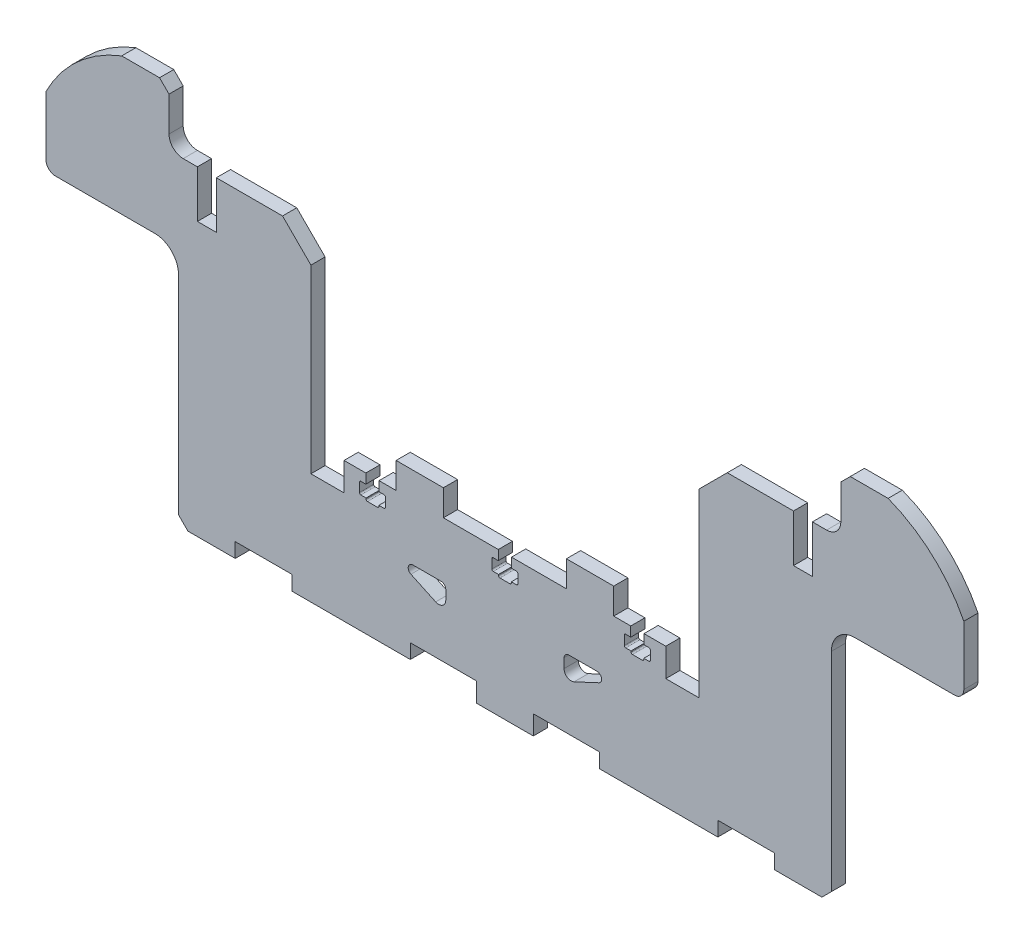
SolidWorks part; units mm, degrees
ref_plane "前视基准面" through (0, 0, 0) normal (0, 0, 1) x (1, 0, 0)
ref_plane "上视基准面" through (0, 0, 0) normal (0, 1, 0) x (1, 0, 0)
ref_plane "右视基准面" through (0, 0, 0) normal (1, 0, 0) x (0, 0, -1)
sketch "草图1" plane through (0, 0, 0) normal (0, 0, 1) x (-1, 0, 0)
  line L2 (-187.1418, -9.2028) -> (-181.9079, -11.6453)
  line L4 (-189.2762, -12.5515) -> (-189.2762, -10.5621)
  line L6 (-182.3308, -13.5515) -> (-188.2762, -13.5515)
  line L8 (-221.6444, -11.6453) -> (-216.4105, -9.2028)
  line L10 (-214.2762, -10.5621) -> (-214.2762, -12.5515)
  line L12 (-215.2762, -13.5515) -> (-221.2216, -13.5515)
  line L188 (-132.7762, 2.0293) -> (-134.7762, 4.0293)
  line L189 (-134.7762, 4.0293) -> (-144.7762, 4.0293)
  line L190 (-144.7762, 4.0293) -> (-144.7762, 0.9485)
  line L191 (-144.7762, 0.9485) -> (-156.7762, 0.9485)
  line L192 (-156.7762, 0.9485) -> (-156.7762, 4.0293)
  line L193 (-156.7762, 4.0293) -> (-181.7762, 4.0293)
  line L194 (-181.7762, 4.0293) -> (-181.7762, 0.9485)
  line L195 (-181.7762, 0.9485) -> (-195.7762, 0.9485)
  line L196 (-195.7762, 0.9485) -> (-195.7762, 5.0293)
  line L197 (-195.7762, 5.0293) -> (-207.7762, 5.0293)
  line L198 (-207.7762, 5.0293) -> (-207.7762, 0.9485)
  line L199 (-207.7762, 0.9485) -> (-221.7762, 0.9485)
  line L200 (-221.7762, 0.9485) -> (-221.7762, 4.0293)
  line L201 (-221.7762, 4.0293) -> (-246.7762, 4.0293)
  line L202 (-246.7762, 4.0293) -> (-246.7762, 0.9485)
  line L203 (-246.7762, 0.9485) -> (-258.7762, 0.9485)
  line L204 (-258.7762, 0.9485) -> (-258.7762, 4.0293)
  line L205 (-258.7762, 4.0293) -> (-268.7762, 4.0293)
  line L206 (-268.7762, 4.0293) -> (-270.7762, 2.0293)
  line L207 (-270.7762, 2.0293) -> (-270.7762, -41.9707)
  line L208 (-275.7762, -46.9707) -> (-296.7762, -46.9707)
  line L209 (-298.7762, -48.9707) -> (-298.7762, -61.4707)
  line L210 (-282.7762, -75.9707) -> (-274.7762, -75.9707)
  line L211 (-274.7762, -75.9707) -> (-272.7762, -73.9707)
  line L212 (-272.7762, -73.9707) -> (-272.7762, -66.6653)
  line L213 (-269.7762, -63.6653) -> (-266.7762, -63.6653)
  line L214 (-266.7762, -63.6653) -> (-266.7762, -53.6653)
  line L215 (-266.7762, -53.6653) -> (-262.7762, -53.6653)
  line L216 (-262.7762, -53.6653) -> (-262.7762, -63.6653)
  line L217 (-262.7762, -63.6653) -> (-248.7762, -63.6653)
  line L218 (-248.7762, -63.6653) -> (-242.7762, -57.6653)
  line L219 (-242.7762, -57.6653) -> (-242.7762, -19.4707)
  line L220 (-242.7762, -19.4707) -> (-235.7762, -19.4707)
  line L221 (-235.7762, -19.4707) -> (-235.7762, -25.4153)
  line L222 (-235.7762, -25.4153) -> (-231.1762, -25.4153)
  line L223 (-231.1762, -25.4153) -> (-231.1762, -23.3707)
  line L224 (-231.1762, -23.3707) -> (-232.2262, -23.3707)
  line L225 (-232.5262, -23.0707) -> (-232.5262, -21.1707)
  line L226 (-232.2262, -20.8707) -> (-231.1262, -20.8707)
  line L227 (-231.1262, -20.8707) -> (-231.1262, -20.6707)
  line L228 (-230.8262, -20.3707) -> (-228.7262, -20.3707)
  line L229 (-228.4262, -20.6707) -> (-228.4262, -20.8707)
  line L230 (-228.4262, -20.8707) -> (-227.3262, -20.8707)
  line L231 (-227.0262, -21.1707) -> (-227.0262, -23.0707)
  line L232 (-227.3262, -23.3707) -> (-228.3762, -23.3707)
  line L233 (-228.3762, -23.3707) -> (-228.3762, -25.4153)
  line L234 (-228.3762, -25.4153) -> (-224.7762, -25.4153)
  line L235 (-224.7762, -25.4153) -> (-224.7762, -30.9153)
  line L236 (-224.7762, -30.9153) -> (-214.7762, -30.9153)
  line L237 (-214.7762, -30.9153) -> (-214.7762, -25.4153)
  line L238 (-214.7762, -25.4153) -> (-203.1762, -25.4153)
  line L239 (-203.1762, -25.4153) -> (-203.1762, -23.3707)
  line L240 (-203.1762, -23.3707) -> (-204.2262, -23.3707)
  line L241 (-204.5262, -23.0707) -> (-204.5262, -21.1707)
  line L242 (-204.2262, -20.8707) -> (-203.1262, -20.8707)
  line L243 (-203.1262, -20.8707) -> (-203.1262, -20.6707)
  line L244 (-202.8262, -20.3707) -> (-200.7262, -20.3707)
  line L245 (-200.4262, -20.6707) -> (-200.4262, -20.8707)
  line L246 (-200.4262, -20.8707) -> (-199.3262, -20.8707)
  line L247 (-199.0262, -21.1707) -> (-199.0262, -23.0707)
  line L248 (-199.3262, -23.3707) -> (-200.3762, -23.3707)
  line L249 (-200.3762, -23.3707) -> (-200.3762, -25.4153)
  line L250 (-200.3762, -25.4153) -> (-188.7762, -25.4153)
  line L251 (-188.7762, -25.4153) -> (-188.7762, -30.9153)
  line L252 (-188.7762, -30.9153) -> (-178.7762, -30.9153)
  line L253 (-178.7762, -30.9153) -> (-178.7762, -25.4153)
  line L254 (-178.7762, -25.4153) -> (-175.1762, -25.4153)
  line L255 (-175.1762, -25.4153) -> (-175.1762, -23.3707)
  line L256 (-175.1762, -23.3707) -> (-176.2262, -23.3707)
  line L257 (-176.5262, -23.0707) -> (-176.5262, -21.1707)
  line L258 (-176.2262, -20.8707) -> (-175.1262, -20.8707)
  line L259 (-175.1262, -20.8707) -> (-175.1262, -20.6707)
  line L260 (-174.8262, -20.3707) -> (-172.7262, -20.3707)
  line L261 (-172.4262, -20.6707) -> (-172.4262, -20.8707)
  line L262 (-172.4262, -20.8707) -> (-171.3262, -20.8707)
  line L263 (-171.0262, -21.1707) -> (-171.0262, -23.0707)
  line L264 (-171.3262, -23.3707) -> (-172.3762, -23.3707)
  line L265 (-172.3762, -23.3707) -> (-172.3762, -25.4153)
  line L266 (-172.3762, -25.4153) -> (-167.7762, -25.4153)
  line L267 (-167.7762, -25.4153) -> (-167.7762, -19.4707)
  line L268 (-167.7762, -19.4707) -> (-160.7762, -19.4707)
  line L269 (-160.7762, -19.4707) -> (-160.7762, -57.6653)
  line L270 (-160.7762, -57.6653) -> (-154.7762, -63.6653)
  line L271 (-154.7762, -63.6653) -> (-140.7762, -63.6653)
  line L272 (-140.7762, -63.6653) -> (-140.7762, -53.6653)
  line L273 (-140.7762, -53.6653) -> (-136.7762, -53.6653)
  line L274 (-136.7762, -53.6653) -> (-136.7762, -63.6653)
  line L275 (-136.7762, -63.6653) -> (-133.7762, -63.6653)
  line L276 (-130.7762, -66.6653) -> (-130.7762, -73.9707)
  line L277 (-130.7762, -73.9707) -> (-128.7762, -75.9707)
  line L278 (-128.7762, -75.9707) -> (-120.7762, -75.9707)
  line L279 (-104.7762, -61.4707) -> (-104.7762, -48.9707)
  line L280 (-106.7762, -46.9707) -> (-127.7762, -46.9707)
  line L281 (-132.7762, -41.9707) -> (-132.7762, 2.0293)
  arc A1 (-187.1418, -9.2028) -> (-189.2762, -10.5621) centre (-187.7762, -10.5621) ccw
  arc A3 (-182.3308, -13.5515) -> (-181.9079, -11.6453) centre (-182.3308, -12.5515) ccw
  arc A5 (-189.2762, -12.5515) -> (-188.2762, -13.5515) centre (-188.2762, -12.5515) ccw
  arc A7 (-214.2762, -10.5621) -> (-216.4105, -9.2028) centre (-215.7762, -10.5621) ccw
  arc A9 (-215.2762, -13.5515) -> (-214.2762, -12.5515) centre (-215.2762, -12.5515) ccw
  arc A11 (-221.6444, -11.6453) -> (-221.2216, -13.5515) centre (-221.2216, -12.5515) ccw
  arc A52 (-275.7762, -46.9707) -> (-270.7762, -41.9707) centre (-275.7762, -41.9707) ccw
  arc A53 (-296.7762, -46.9707) -> (-298.7762, -48.9707) centre (-296.7762, -48.9707) ccw
  arc A54 (-298.7762, -61.4707) -> (-282.7762, -75.9707) centre (-271.9804, -47.9805) ccw
  arc A55 (-269.7762, -63.6653) -> (-272.7762, -66.6653) centre (-269.7762, -66.6653) ccw
  arc A56 (-232.5262, -23.0707) -> (-232.2262, -23.3707) centre (-232.2262, -23.0707) ccw
  arc A57 (-232.2262, -20.8707) -> (-232.5262, -21.1707) centre (-232.2262, -21.1707) ccw
  arc A58 (-230.8262, -20.3707) -> (-231.1262, -20.6707) centre (-230.8262, -20.6707) ccw
  arc A59 (-228.4262, -20.6707) -> (-228.7262, -20.3707) centre (-228.7262, -20.6707) ccw
  arc A60 (-227.0262, -21.1707) -> (-227.3262, -20.8707) centre (-227.3262, -21.1707) ccw
  arc A61 (-227.3262, -23.3707) -> (-227.0262, -23.0707) centre (-227.3262, -23.0707) ccw
  arc A62 (-204.5262, -23.0707) -> (-204.2262, -23.3707) centre (-204.2262, -23.0707) ccw
  arc A63 (-204.2262, -20.8707) -> (-204.5262, -21.1707) centre (-204.2262, -21.1707) ccw
  arc A64 (-202.8262, -20.3707) -> (-203.1262, -20.6707) centre (-202.8262, -20.6707) ccw
  arc A65 (-200.4262, -20.6707) -> (-200.7262, -20.3707) centre (-200.7262, -20.6707) ccw
  arc A66 (-199.0262, -21.1707) -> (-199.3262, -20.8707) centre (-199.3262, -21.1707) ccw
  arc A67 (-199.3262, -23.3707) -> (-199.0262, -23.0707) centre (-199.3262, -23.0707) ccw
  arc A68 (-176.5262, -23.0707) -> (-176.2262, -23.3707) centre (-176.2262, -23.0707) ccw
  arc A69 (-176.2262, -20.8707) -> (-176.5262, -21.1707) centre (-176.2262, -21.1707) ccw
  arc A70 (-174.8262, -20.3707) -> (-175.1262, -20.6707) centre (-174.8262, -20.6707) ccw
  arc A71 (-172.4262, -20.6707) -> (-172.7262, -20.3707) centre (-172.7262, -20.6707) ccw
  arc A72 (-171.0262, -21.1707) -> (-171.3262, -20.8707) centre (-171.3262, -21.1707) ccw
  arc A73 (-171.3262, -23.3707) -> (-171.0262, -23.0707) centre (-171.3262, -23.0707) ccw
  arc A74 (-130.7762, -66.6653) -> (-133.7762, -63.6653) centre (-133.7762, -66.6653) ccw
  arc A75 (-120.7762, -75.9707) -> (-104.7762, -61.4707) centre (-131.572, -47.9805) ccw
  arc A76 (-104.7762, -48.9707) -> (-106.7762, -46.9707) centre (-106.7762, -48.9707) ccw
  arc A77 (-132.7762, -41.9707) -> (-127.7762, -46.9707) centre (-127.7762, -41.9707) ccw
extrude "凸台-拉伸1" add sketch "草图1" along normal blind 3
ref_plane "基准面1" through (201.7762, 0, 0) normal (-1, 0, 0) x (0, 0, 1)
